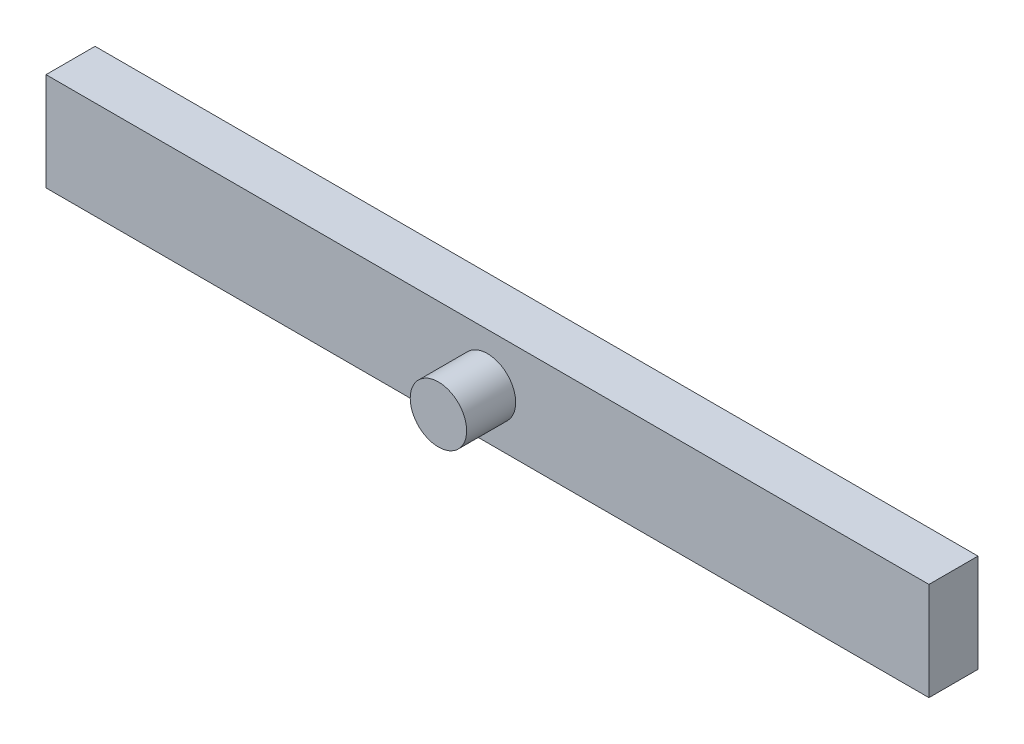
SolidWorks part; units mm, degrees
ref_plane "Front Plane" through (0, 0, 0) normal (0, 0, 1) x (1, 0, 0)
ref_plane "Top Plane" through (0, 0, 0) normal (0, 1, 0) x (1, 0, 0)
ref_plane "Right Plane" through (0, 0, 0) normal (1, 0, 0) x (0, 0, -1)
sketch "Sketch1" plane through (0, 0, 0) normal (0, 0, 1) x (1, 0, 0)
  line L1 (0, 5) -> (45, 5)
  line L2 (45, 5) -> (45, -5)
  line L3 (45, -5) -> (-45, -5)
  line L4 (-45, -5) -> (-45, 5)
  line L5 (-45, 5) -> (0, 5)
extrude "Boss-Extrude2" add sketch "Sketch1" against normal blind 5
sketch "Sketch2" plane through (0, 0, 0) normal (0, 0, 1) x (1, 0, 0)
  circle A0 centre (0, 0) radius 2.875
extrude "Boss-Extrude3" add sketch "Sketch2" along normal blind 5
